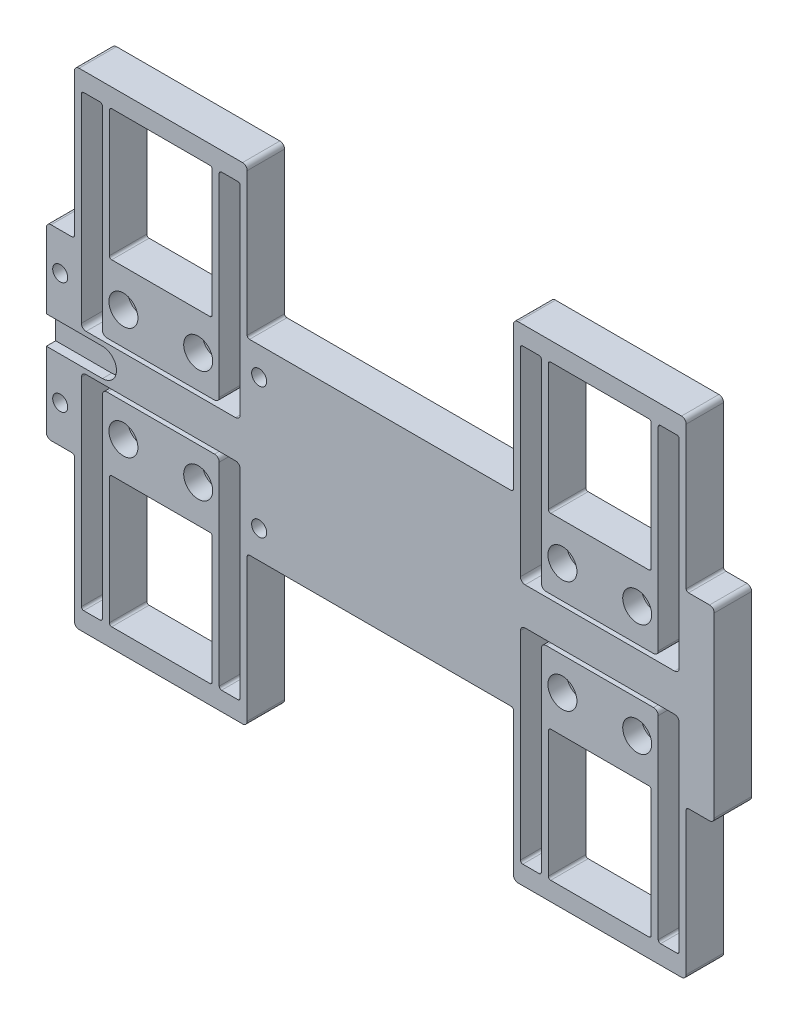
SolidWorks part; units mm, degrees
material "6061 Alloy"
ref_plane "Front Plane" through (0, 0, 0) normal (0, 0, 1) x (1, 0, 0)
ref_plane "Top Plane" through (0, 0, 0) normal (0, 1, 0) x (1, 0, 0)
ref_plane "Right Plane" through (0, 0, 0) normal (1, 0, 0) x (0, 0, -1)
sketch "Sketch6" plane through (0, 12.7, 0) normal (0, 0, -1) x (-1, 0, 0)
  line L0 (0, -12.7) -> (0, -44.45) construction
  line L1 (0, -12.7) -> (-113.411, -12.7) construction
  line L2 (-94.3927, -88.9) -> (-92.0115, -88.9) construction
  line L3 (-45.212, -44.45) -> (45.212, -44.45)
  line L4 (-57.0865, -88.9) -> (-54.7053, -88.9) construction
  line L5 (-45.212, 69.85) -> (-45.212, 19.05)
  line L6 (-103.886, 69.85) -> (-45.212, 69.85)
  line L7 (-103.886, 19.05) -> (-103.886, 69.85)
  line L8 (-94.3927, -88.9) -> (-94.3927, -20.6375)
  line L9 (-54.7053, -20.6375) -> (-94.3927, -20.6375)
  line L10 (-113.411, 19.05) -> (-103.886, 19.05)
  line L11 (-101.5048, -6.35) -> (-47.5933, -6.35)
  line L12 (-92.0115, 19.05) -> (-57.0865, 19.05)
  line L13 (-92.0115, 19.05) -> (-92.0115, 63.5)
  line L14 (-57.0865, 63.5) -> (-92.0115, 63.5)
  line L15 (-57.0865, 19.05) -> (-57.0865, 63.5)
  line L16 (-47.5933, 63.5) -> (-54.7053, 63.5)
  line L17 (-47.5933, -6.35) -> (-47.5933, 63.5)
  line L18 (-54.7053, 63.5) -> (-54.7053, -4.7625)
  line L19 (-101.5048, -88.9) -> (-94.3927, -88.9)
  line L20 (-101.5048, -6.35) -> (-101.5048, 63.5)
  line L21 (-101.5048, 63.5) -> (-94.3927, 63.5)
  line L22 (-54.7053, -4.7625) -> (-94.3927, -4.7625)
  line L23 (-94.3927, 63.5) -> (-94.3927, -4.7625)
  line L24 (-45.212, 19.05) -> (45.212, 19.05)
  line L25 (45.212, -95.25) -> (45.212, -44.45)
  line L26 (103.886, -95.25) -> (45.212, -95.25)
  line L27 (103.886, -44.45) -> (103.886, -95.25)
  line L28 (113.411, -44.45) -> (103.886, -44.45)
  line L29 (113.411, 19.05) -> (113.411, -44.45)
  line L30 (101.5048, -19.05) -> (47.5933, -19.05)
  line L31 (92.0115, -44.45) -> (57.0865, -44.45)
  line L32 (92.0115, -44.45) -> (92.0115, -88.9)
  line L33 (57.0865, -88.9) -> (92.0115, -88.9)
  line L34 (57.0865, -44.45) -> (57.0865, -88.9)
  line L35 (47.5932, -88.9) -> (54.7052, -88.9)
  line L36 (47.5933, -19.05) -> (47.5932, -88.9)
  line L37 (54.7052, -88.9) -> (54.7053, -20.6375)
  line L38 (101.5048, -19.05) -> (101.5047, -88.9)
  line L39 (94.3927, 63.5) -> (94.3927, -4.7625)
  line L40 (-101.5048, -19.05) -> (-101.5048, -88.9)
  line L41 (-54.7053, -88.9) -> (-54.7053, -20.6375)
  line L42 (-47.5933, -19.05) -> (-47.5932, -88.9)
  line L43 (-47.5932, -88.9) -> (-54.7053, -88.9)
  line L44 (-57.0865, -44.45) -> (-57.0865, -88.9)
  line L45 (-57.0865, -88.9) -> (-92.0115, -88.9)
  line L46 (-92.0115, -44.45) -> (-92.0115, -88.9)
  line L47 (-92.0115, -44.45) -> (-57.0865, -44.45)
  line L48 (-74.549, -19.05) -> (-74.549, -88.9) construction
  line L49 (-101.5048, -19.05) -> (-47.5933, -19.05)
  line L50 (-113.411, 19.05) -> (-113.411, -44.45)
  line L51 (-113.411, -44.45) -> (-103.886, -44.45)
  line L52 (-103.886, -44.45) -> (-103.886, -95.25)
  line L53 (-103.886, -95.25) -> (-45.212, -95.25)
  line L54 (-45.212, -95.25) -> (-45.212, -44.45)
  line L55 (54.7053, -4.7625) -> (94.3927, -4.7625)
  line L56 (101.5047, 63.5) -> (94.3927, 63.5)
  line L57 (101.5048, -6.35) -> (101.5047, 63.5)
  line L58 (101.5047, -88.9) -> (94.3927, -88.9)
  line L59 (54.7052, 63.5) -> (54.7053, -4.7625)
  line L60 (47.5933, -6.35) -> (47.5932, 63.5)
  line L61 (47.5932, 63.5) -> (54.7052, 63.5)
  line L62 (57.0865, 19.05) -> (57.0865, 63.5)
  line L63 (57.0865, 63.5) -> (92.0115, 63.5)
  line L64 (92.0115, 19.05) -> (92.0115, 63.5)
  line L65 (92.0115, 19.05) -> (57.0865, 19.05)
  line L66 (101.5048, -6.35) -> (47.5933, -6.35)
  line L67 (113.411, 19.05) -> (103.886, 19.05)
  line L68 (54.7053, -20.6375) -> (94.3927, -20.6375)
  line L69 (94.3927, -88.9) -> (94.3927, -20.6375)
  line L70 (103.886, 19.05) -> (103.886, 69.85)
  line L71 (103.886, 69.85) -> (45.212, 69.85)
  line L72 (45.212, 69.85) -> (45.212, 19.05)
  line L74 (-47.5932, -88.9) -> (-45.212, -88.9) construction
  point P6 (-74.549, 63.5)
  point P43 (74.549, -88.9)
  point P62 (74.549, 63.5)
  point P76 (-74.549, -88.9)
  dimension "D2" = 226.822
  dimension "D3" = 12.7
  dimension "D4" = 1.5875
  dimension "D5" = 63.5
  dimension "D6" = 149.098
  dimension "D7" = 44.45
  dimension "D8" = 34.925
  dimension "D9" = 2.3813
  dimension "D10" = 6.35
  dimension "D11" = 7.112
  dimension "D12" = 63.5
extrude "Extrude1" add sketch "Sketch6" along normal mid plane 12.7
hole_wizard "Cross feed 1/4 counterbores" positions "Sketch8" profile "Sketch7" counterbore size "1/4" standard "Ansi Inch" end condition through all
sketch "Sketch8" plane through (0, 0, 6.35) normal (0, 0, 1) x (1, 0, 0)
  line L5 (113.411, 0) -> (-113.411, 0) construction
  line L6 (113.411, 31.75) -> (113.411, -31.75) construction
  line L7 (-113.411, -31.75) -> (-113.411, 31.75) construction
  line L8 (0, -31.75) -> (0, 31.75) construction
  line L9 (45.212, -31.75) -> (-45.212, -31.75) construction
  line L10 (-45.212, 31.75) -> (45.212, 31.75) construction
  line L16 (87.249, 19.05) -> (61.849, 19.05) construction
  line L17 (54.7053, 7.9375) -> (94.3927, 7.9375) construction
  line L18 (54.7053, 7.9375) -> (94.3927, 7.9375) construction
  line L20 (74.549, 19.05) -> (74.549, 7.9375) construction
  point P3 (61.849, 19.05)
  point P5 (87.249, 19.05)
  point P93 (87.249, -19.05)
  point P94 (61.849, -19.05)
  point P95 (-61.849, -19.05)
  point P96 (-87.249, -19.05)
  point P97 (-87.249, 19.05)
  point P98 (-61.849, 19.05)
  dimension "D1" = 25.4
  dimension "D2" = 19.05
  dimension "D3" = 74.549
sketch "Sketch7" plane through (61.849, 19.05, 6.35) normal (1, 0, 0) x (0, -1, 0)
  line L0 (0, 0) -> (0, 12.7)
  line L1 (0, 12.7) -> (3.3782, 12.7)
  line L3 (3.3782, 12.7) -> (3.3782, 6.35)
  line L4 (3.3782, 6.35) -> (4.9212, 6.35)
  line L5 (4.9212, 6.35) -> (4.9212, 0)
  line L7 (4.9212, 0) -> (0, 0)
  line L11 (0, -6.35) -> (0, 107.95) construction
  dimension "Thru Hole Dia." = 6.7564
  dimension "Thru Hole Depth" = 12.7
  dimension "C'Bore Dia." = 9.8425
  dimension "C'Bore Depth" = 6.35
hole_wizard "1/4 screw mounting holes" positions "Sketch10" profile "Sketch9" tap size "1/4-20" standard "Ansi Inch" end condition through all
sketch "Sketch10" plane through (0, 0, 6.35) normal (0, 0, 1) x (1, 0, 0)
  line L0 (0, 31.75) -> (0, -31.75) construction
  line L1 (-45.212, 31.75) -> (45.212, 31.75) construction
  line L2 (45.212, -31.75) -> (-45.212, -31.75) construction
  line L3 (113.411, 0) -> (-113.411, 0) construction
  line L4 (113.411, 31.75) -> (113.411, -31.75) construction
  line L5 (-113.411, -31.75) -> (-113.411, 31.75) construction
  point P1 (-108.712, 19.05)
  point P4 (-41.148, 22.225)
  point P25 (-41.148, -22.225)
  point P26 (-108.712, -19.05)
  dimension "D1" = 41.148
  dimension "D2" = 108.712
  dimension "D3" = 19.05
  dimension "D4" = 44.45
sketch "Sketch9" plane through (-108.712, 19.05, 6.35) normal (1, 0, 0) x (0, -1, 0)
  line L0 (0, 0) -> (0, 12.7)
  line L1 (0, 12.7) -> (2.5527, 12.7)
  line L2 (2.5527, 12.7) -> (2.5527, 0)
  line L5 (2.5527, 0) -> (0, 0)
  line L11 (0, -6.35) -> (0, 107.95) construction
  dimension "Thru Tap Drill Dia." = 5.1054
  dimension "Thru Tap Drill Depth" = 12.7
cosmetic thread "Hole Thread1" parameters "D2"=6.35
cosmetic thread "Hole Thread2" parameters "D2"=6.35
cosmetic thread "Hole Thread3" parameters "D2"=6.35
cosmetic thread "Hole Thread4" parameters "D2"=6.35
fillet "Flexure fillets" radius 0.7937 40 edges at (45.212, 31.75, 0) (-103.886, 31.75, 0) (103.886, 31.75, 0) (-45.212, 31.75, 0) (-103.886, -31.75, 0) (45.212, -31.75, 0) (103.886, -31.75, 0) (-45.212, -31.75, 0) (-92.0115, -31.75, 0) (57.0865, -31.75, 0) (-57.0865, -31.75, 0) (92.0115, -31.75, 0) (-57.0865, 31.75, 0) (92.0115, 31.75, 0) (-92.0115, 31.75, 0) (57.0865, 31.75, 0) (47.5932, -76.2, 0) (57.0865, -76.2, 0) (94.3927, -76.2, 0) (54.7053, -76.2, 0) (92.0115, -76.2, 0) (101.5048, -76.2, 0) (-47.5932, -76.2, 0) (-57.0865, -76.2, 0) (-94.3927, -76.2, 0) (-54.7052, -76.2, 0) (-92.0115, -76.2, 0) (-101.5047, -76.2, 0) (94.3927, 76.2, 0) (57.0865, 76.2, 0) (47.5933, 76.2, 0) (-54.7052, 76.2, 0) (-92.0115, 76.2, 0) (-101.5047, 76.2, 0) (101.5048, 76.2, 0) (92.0115, 76.2, 0) (54.7053, 76.2, 0) (-94.3927, 76.2, 0) (-57.0865, 76.2, 0) (-47.5932, 76.2, 0)
fillet "Safety radius" radius 1.5875 28 edges at (-47.5933, -6.35, 0) (101.5048, -6.35, 0) (-101.5048, -6.35, 0) (47.5933, -6.35, 0) (-101.5048, 6.35, 0) (47.5933, 6.35, 0) (101.5048, 6.35, 0) (-47.5933, 6.35, 0) (113.411, 31.75, 0) (103.886, 82.55, 0) (45.212, 82.55, 0) (-45.212, 82.55, 0) (-103.886, 82.55, 0) (-113.411, 31.75, 0) (-113.411, -31.75, 0) (113.411, -31.75, 0) (-45.212, -82.55, 0) (103.886, -82.55, 0) (-103.886, -82.55, 0) (45.212, -82.55, 0) (-94.3927, 7.9375, 0) (54.7053, 7.9375, 0) (54.7053, -7.9375, 0) (94.3927, -7.9375, 0) (94.3927, 7.9375, 0) (-54.7053, 7.9375, 0) (-54.7053, -7.9375, 0) (-94.3927, -7.9375, 0)
sketch "Sketch11" plane through (0, 0, 6.35) normal (0, 0, -1) x (-1, 0, 0)
  line L0 (113.411, -30.1625) -> (113.411, 30.1625) construction
  line L1 (113.411, -4.7625) -> (94.361, -4.7625)
  line L2 (113.411, -4.7625) -> (113.411, 4.7625)
  line L3 (113.411, 4.7625) -> (94.361, 4.7625)
  arc A0 (94.361, 4.7625) -> (94.361, -4.7625) centre (94.361, 0) ccw
  circle A1 centre (94.361, 0) radius 4.7625 construction
  dimension "D1" = 9.525
  dimension "D2" = 19.05
extrude "Extrude2" cut sketch "Sketch11" along normal blind 3.175
